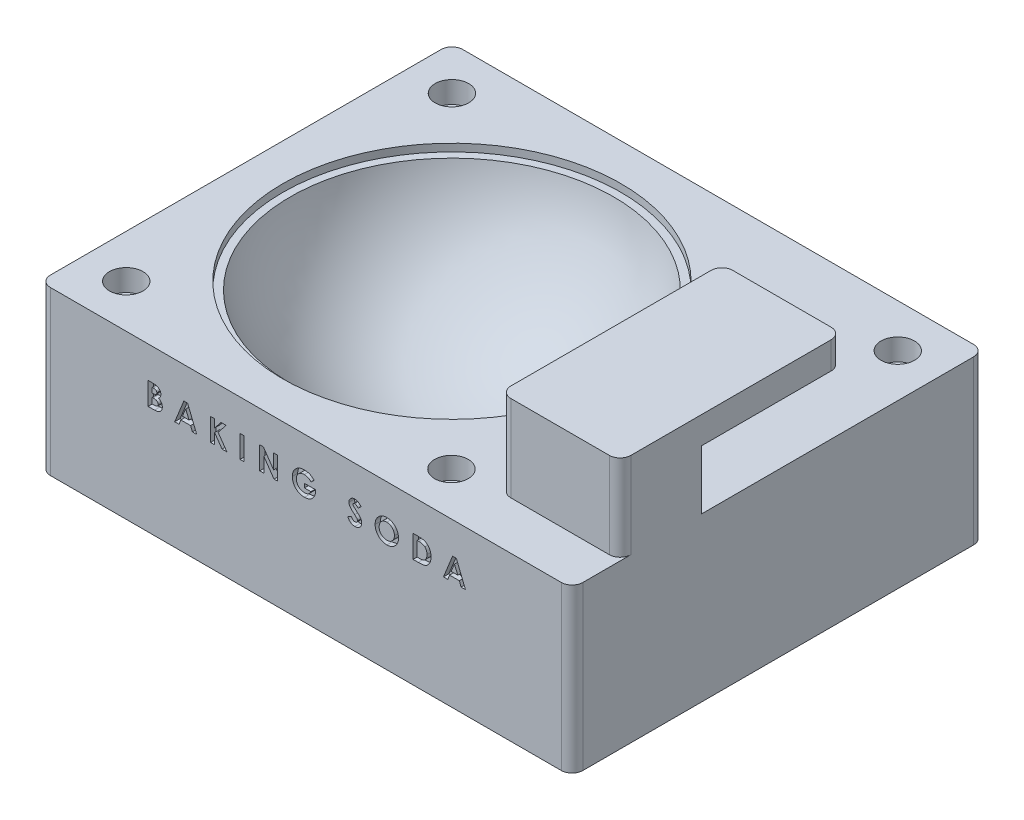
SolidWorks part; units mm, degrees
material "ABS"
ref_plane "Front Plane" through (0, 0, 0) normal (0, 0, 1) x (1, 0, 0)
ref_plane "Top Plane" through (0, 0, 0) normal (0, 1, 0) x (1, 0, 0)
ref_plane "Right Plane" through (0, 0, 0) normal (1, 0, 0) x (0, 0, -1)
sketch "Sketch1" plane through (0, 0, 0) normal (0, 0, 1) x (1, 0, 0)
  line L1 (-71.1509, 19.8885) -> (53.7917, 19.8885)
  line L2 (-71.1509, 19.8885) -> (-71.1509, -18.3385)
  line L3 (-71.1509, -18.3385) -> (53.7917, -18.3385)
  line L4 (53.7917, 19.8885) -> (53.7917, -18.3385)
  dimension "D1" = 124.9426
  dimension "D2" = 38.227
extrude "Boss-Extrude1" add sketch "Sketch1" along normal blind 96.7486
ref_plane "Plane1" through (0, 0, 48.3743) normal (0, 0, 1) x (1, 0, 0)
sketch "Sketch2" plane through (0, 0, 48.3743) normal (0, 0, 1) x (1, 0, 0)
  line L0 (-62.4641, 19.8885) -> (-62.4641, 18.1105)
  line L1 (53.7917, 19.8885) -> (-71.1509, 19.8885) construction
  line L2 (-62.4641, 18.1105) -> (-60.6861, 18.1105)
  line L3 (-60.6861, 18.1105) -> (-60.6861, -12.4965)
  line L4 (-60.6861, -12.4965) -> (15.1329, -12.4965)
  line L5 (15.1329, -12.4965) -> (15.1329, 18.1105)
  line L6 (15.1329, 18.1105) -> (16.9109, 18.1105)
  line L7 (16.9109, 18.1105) -> (16.9109, 19.8885)
  line L8 (16.9109, 19.8885) -> (-62.4641, 19.8885)
  line L9 (-71.1509, 19.8885) -> (-71.1509, -18.3385) construction
  line L11 (-22.7766, 19.8885) -> (-22.7766, -12.4965)
  arc A0 (-60.6861, 18.1105) -> (15.1329, 18.1105) centre (-22.7766, 26.2841) ccw
  point P6 (-22.7766, -12.4965)
  point P11 (-22.7766, 19.8885)
  point P14 (-62.4641, 18.9995)
  dimension "D6" = 38.7806
  dimension "D1" = 1.778
  dimension "D2" = 30.607
  dimension "D3" = 75.819
  dimension "D4" = 79.375
  dimension "D5" = 8.6868
revolve "Cut-Revolve1" cut sketch "Sketch2" angle 360 about L11
sketch "Sketch3" plane through (0, 0, 48.3743) normal (0, 0, 1) x (1, 0, 0)
  line L0 (-25.9516, 19.8885) -> (-25.9516, -18.3385)
  line L1 (-25.9516, 19.8885) -> (-19.6016, 19.8885)
  line L2 (-19.6016, 19.8885) -> (-19.6016, -18.3385)
  line L3 (-19.6016, -18.3385) -> (-25.9516, -18.3385)
  line L5 (-22.7766, -991.401) -> (-22.7766, 49008.599)
  line L6 (16.9109, 19.8885) -> (-62.4641, 19.8885) construction
  line L7 (-22.7766, 19.8885) -> (-22.7766, -12.4965) construction
  line L8 (-71.1509, -18.3385) -> (53.7917, -18.3385) construction
  point P2 (-22.7766, 19.8885)
  dimension "D2" = 6.35
revolve "Cut-Revolve3" cut sketch "Sketch3" angle 360 about L5
sketch "Sketch6" plane through (0, 19.8885, 0) normal (0, 1, 0) x (1, 0, 0)
  line L0 (53.7917, -85.4772) -> (19.2604, -85.4772)
  line L1 (53.7917, -96.7486) -> (53.7917, 0) construction
  line L2 (19.2604, -85.4772) -> (19.2604, -58.5343)
  line L3 (19.2604, -58.5343) -> (53.7917, -66.4272)
  line L4 (53.7917, -66.4272) -> (53.7917, -85.4772)
  line L5 (-946.2083, -48.3743) -> (49053.7917, -48.3743) construction
  line L6 (41.4854, -48.3743) -> (41.4854, 49951.6257) construction
  circle A0 centre (-22.7766, -48.3743) radius 39.6875 construction
  point P9 (53.7917, -48.3743)
  point P13 (41.4854, -63.6143)
  dimension "D1" = 10.16
  dimension "D2" = 15.24
  dimension "D3" = 42.037
  dimension "D4" = 19.05
  dimension "D5" = 22.225
extrude "Boss-Extrude3" add sketch "Sketch6" along normal blind 13.843
sketch "Sketch7" plane through (0, 33.7315, 0) normal (0, 1, 0) x (1, 0, 0)
  line L0 (53.7917, -66.4272) -> (53.7917, 0) construction
  line L1 (19.2604, -85.4772) -> (53.7917, -85.4772)
  line L2 (19.2604, -85.4772) -> (19.2604, -33.4072)
  line L3 (19.2604, -33.4072) -> (53.7917, -33.4072)
  line L4 (53.7917, -85.4772) -> (53.7917, -33.4072)
  dimension "D1" = 33.02
extrude "Boss-Extrude4" add sketch "Sketch7" along normal blind 6.35
sketch "Sketch8" plane through (0, 0, 85.4772) normal (0, 0, 1) x (1, 0, 0)
  line L0 (19.2604, 19.8885) -> (53.7917, 19.8885) construction
  line L1 (19.2604, 40.0815) -> (25.6104, 40.0815)
  line L2 (19.2604, 40.0815) -> (19.2604, 19.8885)
  line L3 (19.2604, 19.8885) -> (25.6104, 19.8885)
  line L4 (25.6104, 40.0815) -> (25.6104, 19.8885)
  dimension "D1" = 6.35
extrude "Cut-Extrude1" cut sketch "Sketch8" against normal through all
fillet "Fillet1" radius 2.54 4 edges at (53.7917, 0.775, 0) (53.7917, 0.775, 96.7486) (-71.1509, 0.775, 0) (-71.1509, 0.775, 96.7486)
fillet "Fillet2" radius 2.54 4 edges at (53.7917, 29.985, 85.4772) (25.6104, 29.985, 85.4772) (25.6104, 36.9065, 33.4072) (53.7917, 36.9065, 33.4072)
sketch "Sketch9" plane through (0, 19.8885, 0) normal (0, 1, 0) x (1, 0, 0)
  line L0 (51.2517, 0) -> (-68.6109, 0) construction
  line L1 (-71.1509, -94.2086) -> (-71.1509, -2.54) construction
  line L2 (51.2517, -96.7486) -> (-68.6109, -96.7486) construction
  line L3 (25.4834, 0) -> (25.4834, -96.7486) construction
  line L4 (53.7917, -66.4272) -> (53.7917, -2.54) construction
  line L5 (53.7917, -82.9372) -> (53.7917, -35.9472) construction
  line L6 (53.7917, -94.2086) -> (53.7917, -82.9372) construction
  circle A0 centre (-60.9909, -10.16) radius 2.54
  circle A1 centre (-60.9909, -86.5886) radius 2.54
  circle A2 centre (15.3234, -86.5886) radius 2.54
  circle A3 centre (43.6317, -10.16) radius 2.54
  circle A5 centre (-22.7766, -48.3743) radius 3.175 construction
  dimension "D1" = 5.08
  dimension "D4" = 10.16
  dimension "D5" = 10.16
  dimension "D6" = 10.16
  dimension "D7" = 10.16
  dimension "D8" = 48.26
  dimension "D10" = 10.16
  dimension "D2" = 10.16
  dimension "D3" = 10.16
  dimension "D9" = 10.16
extrude "Cut-Extrude2" cut sketch "Sketch9" against normal through all
sketch "Sketch10" plane through (0, 0, 96.7486) normal (0, 0, 1) x (1, 0, 0)
  line L0 (-68.6109, 7.1885) -> (51.2517, 7.1885) construction
  line L1 (-68.6109, 19.8885) -> (-68.6109, -18.3385) construction
  line L2 (51.2517, -18.3385) -> (51.2517, 19.8885) construction
  line L3 (51.2517, 19.8885) -> (-68.6109, 19.8885) construction
  text T0 "<b>BAKING SODA</b>" font "Century Gothic" height in points 20
  dimension "D1" = 12.7
extrude "Cut-Extrude3" cut sketch "Sketch10" against normal blind 1.27
sketch "Sketch11" plane through (0, 19.8885, 0) normal (0, 1, 0) x (1, 0, 0)
  circle A0 centre (-60.9909, -10.16) radius 3.937
  circle A1 centre (43.6317, -10.16) radius 3.937
  circle A2 centre (-60.9909, -86.5886) radius 3.937
  circle A3 centre (15.3234, -86.5886) radius 3.937
  dimension "D1" = 7.874
  dimension "D2" = 7.874
  dimension "D3" = 7.874
  dimension "D4" = 7.874
extrude "Cut-Extrude4" cut sketch "Sketch11" against normal blind 5.08
sketch "Sketch12" plane through (0, 0, 0) normal (0, 0, -1) x (-1, 0, 0)
  line L0 (-51.2517, 0.775) -> (68.6109, 0.775) construction
  line L1 (-51.2517, 19.8885) -> (-51.2517, -18.3385) construction
  line L2 (68.6109, -18.3385) -> (68.6109, 19.8885) construction
  text T0 "<b>BAKING SODA</b>" font "Century Gothic" height in points 20
extrude "Cut-Extrude5" cut sketch "Sketch12" against normal blind 1.27
